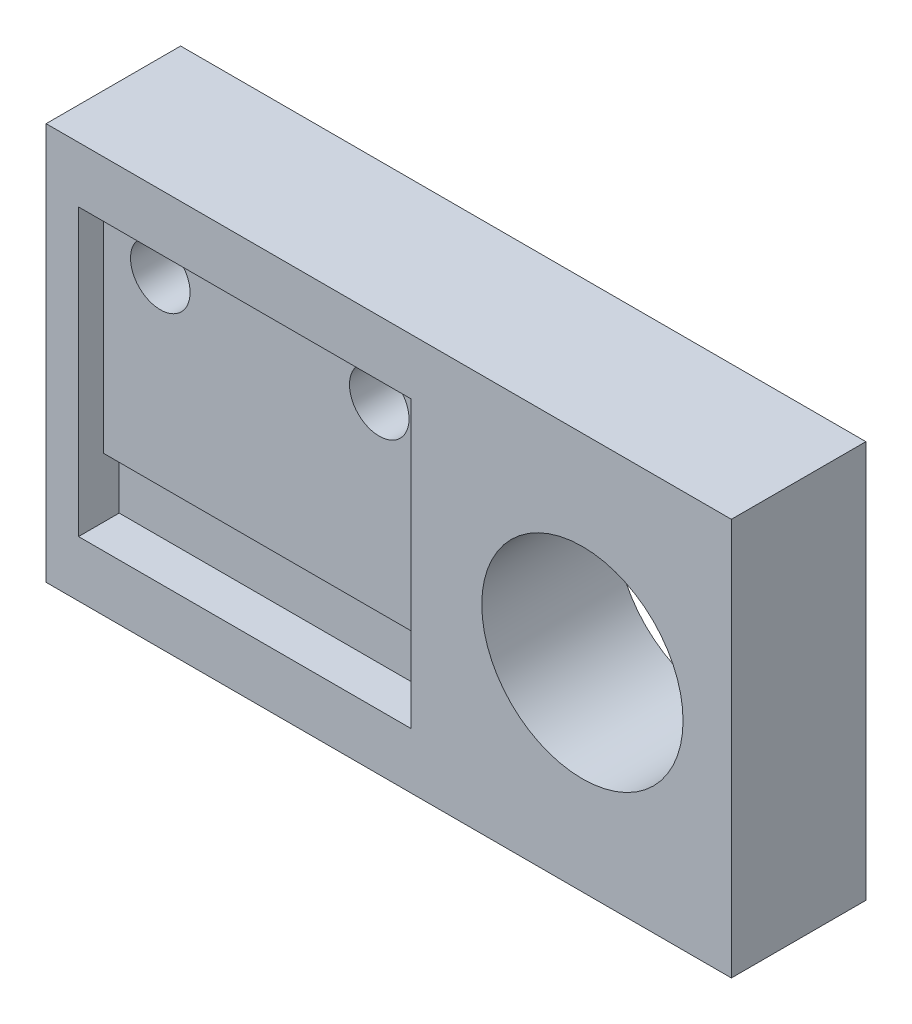
SolidWorks part; units mm, degrees
ref_plane "Front Plane" through (0, 0, 0) normal (0, 0, 1) x (1, 0, 0)
ref_plane "Top Plane" through (0, 0, 0) normal (0, 1, 0) x (1, 0, 0)
ref_plane "Right Plane" through (0, 0, 0) normal (1, 0, 0) x (0, 0, -1)
sketch "Sketch1" plane through (0, 0, 0) normal (0, 0, 1) x (1, 0, 0)
  line L0 (19.7, 12.7) -> (34.29, 12.7) construction
  line L1 (0, 0) -> (43.815, 0)
  line L2 (0, 0) -> (0, 25.4)
  line L3 (0, 25.4) -> (43.815, 25.4)
  line L4 (43.815, 0) -> (43.815, 25.4)
  line L5 (5.7, 19.05) -> (19.7, 19.05) construction
  line L6 (5.7, 19.05) -> (5.7, 6.35) construction
  line L7 (5.7, 6.35) -> (19.7, 6.35) construction
  line L8 (19.7, 19.05) -> (19.7, 6.35) construction
  line L9 (12.7, 19.05) -> (12.7, 25.4) construction
  line L10 (12.7, 6.35) -> (12.7, 0) construction
  line L11 (1.27, 24.13) -> (1.27, 25.4) construction
  line L12 (24.13, 1.27) -> (1.27, 1.27) construction
  line L13 (24.13, 1.27) -> (24.13, 24.13) construction
  line L14 (24.13, 24.13) -> (1.27, 24.13) construction
  line L15 (1.27, 1.27) -> (1.27, 24.13) construction
  line L16 (24.13, 1.27) -> (1.27, 24.13) construction
  line L17 (24.13, 24.13) -> (1.27, 1.27) construction
  line L18 (1.27, 24.13) -> (0, 24.13) construction
  circle A0 centre (5.7, 19.05) radius 1.904
  circle A1 centre (19.7, 19.05) radius 1.904
  circle A2 centre (19.7, 6.35) radius 1.904 construction
  circle A3 centre (5.7, 6.35) radius 1.904 construction
  circle A4 centre (34.29, 12.7) radius 6.435
  point P20 (12.7, 12.7)
  dimension "D1" = 12.87
  dimension "D2" = 3.808
  dimension "D3" = 12.7
  dimension "D4" = 14
  dimension "D5" = 25.4
  dimension "D6" = 22.86
  dimension "D7" = 1.27
  dimension "D8" = 43.815
  dimension "D9" = 9.525
extrude "Boss-Extrude1" add sketch "Sketch1" along normal blind 4
sketch "Sketch2" plane through (0, 0, 4) normal (0, 0, 1) x (1, 0, 0)
  line L0 (5.7, 19.05) -> (19.7, 19.05) construction
  line L1 (12.7, 19.05) -> (12.7, 12.7) construction
  line L3 (2.073, 3.573) -> (23.327, 3.573)
  line L4 (0, 25.4) -> (0, 0)
  line L5 (0, 0) -> (43.815, 0)
  line L6 (43.815, 0) -> (43.815, 25.4)
  line L7 (43.815, 25.4) -> (0, 25.4)
  line L8 (0, 25.4) -> (0, 0)
  line L9 (0, 0) -> (43.815, 0)
  line L10 (43.815, 0) -> (43.815, 25.4)
  line L11 (43.815, 25.4) -> (0, 25.4)
  line L12 (2.073, 3.573) -> (2.073, 21.827)
  line L13 (2.073, 21.827) -> (23.327, 21.827)
  line L14 (23.327, 3.573) -> (23.327, 21.827)
  line L15 (2.073, 3.573) -> (23.327, 21.827) construction
  line L16 (2.073, 21.827) -> (23.327, 3.573) construction
  circle A0 centre (34.29, 12.7) radius 6.435 construction
  circle A1 centre (34.29, 12.7) radius 6.435
  point P12 (12.7, 12.7)
  point P13 (12.7, 12.7)
  point P23 (0, 0)
  dimension "D2" = 21.254
  dimension "D3" = 18.254
  dimension "D1" = 0
extrude "Boss-Extrude2" add sketch "Sketch2" along normal blind 1.6
sketch "Sketch3" plane through (0, 0, 0) normal (0, 0, -1) x (-1, 0, 0)
  line L1 (-16.569, 17.2423) -> (-16.569, 20.8577)
  line L2 (-16.569, 20.8577) -> (-19.7, 22.6654)
  line L3 (-19.7, 22.6654) -> (-22.831, 20.8577)
  line L4 (0, 0) -> (0, 25.4)
  line L5 (0, 25.4) -> (-43.815, 25.4)
  line L6 (-43.815, 25.4) -> (-43.815, 0)
  line L7 (-43.815, 0) -> (0, 0)
  line L8 (0, 0) -> (0, 25.4)
  line L9 (0, 25.4) -> (-43.815, 25.4)
  line L10 (-43.815, 25.4) -> (-43.815, 0)
  line L11 (-43.815, 0) -> (0, 0)
  line L12 (-22.831, 20.8577) -> (-22.831, 17.2423)
  line L13 (-22.831, 17.2423) -> (-19.7, 15.4346)
  line L14 (-19.7, 15.4346) -> (-16.569, 17.2423)
  line L15 (-2.569, 20.8577) -> (-5.7, 22.6654)
  line L16 (-5.7, 22.6654) -> (-8.831, 20.8577)
  line L17 (-8.831, 20.8577) -> (-8.831, 17.2423)
  line L18 (-8.831, 17.2423) -> (-5.7, 15.4346)
  line L19 (-5.7, 15.4346) -> (-2.569, 17.2423)
  line L20 (-2.569, 17.2423) -> (-2.569, 20.8577)
  circle A0 centre (-34.29, 12.7) radius 6.435 construction
  circle A1 centre (-34.29, 12.7) radius 6.435
  circle A2 centre (-19.7, 19.05) radius 3.131 construction
  circle A3 centre (-5.7, 19.05) radius 3.131 construction
  circle A6 centre (-5.7, 19.05) radius 1.904 construction
  dimension "D2" = 6.262
  dimension "D1" = 0
extrude "Boss-Extrude3" add sketch "Sketch3" along normal blind 3
sketch "Sketch5" plane through (0, 0, 4) normal (0, 0, 1) x (1, 0, 0)
  line L0 (2.073, 21.827) -> (2.073, 3.573) construction
  line L1 (2.073, 7.383) -> (23.327, 7.383)
  line L2 (2.073, 7.383) -> (2.073, 3.573)
  line L3 (2.073, 3.573) -> (23.327, 3.573)
  line L4 (23.327, 7.383) -> (23.327, 3.573)
  dimension "D1" = 3.81
extrude "Cut-Extrude1" cut sketch "Sketch5" against normal blind 1
